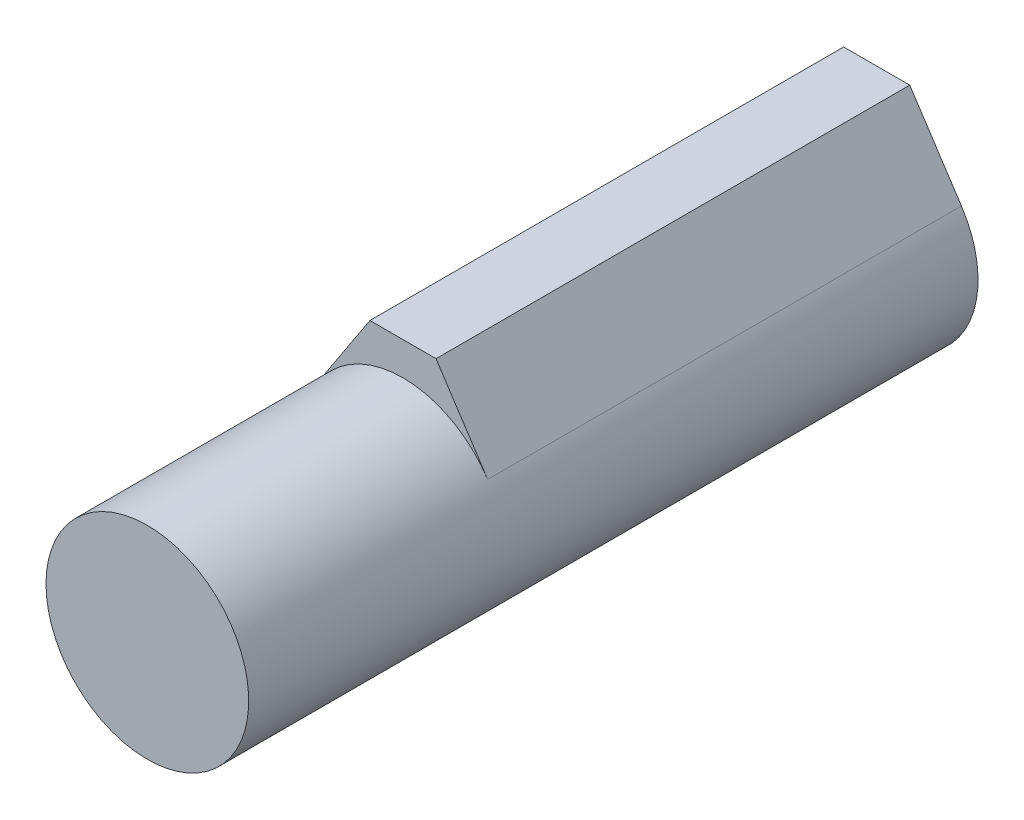
SolidWorks part; units mm, degrees
other "标注1"
sketch "草图4" plane through (-9.2, -9.2, 66.2) normal (-0.7475, -0.0957, 0.6574) x (0.6562, 0.0477, 0.7531)
ref_plane "前视基准面" through (0, 0, 0) normal (0, 0, 1) x (1, 0, 0)
ref_plane "上视基准面" through (0, 0, 0) normal (0, 1, 0) x (1, 0, 0)
ref_plane "右视基准面" through (0, 0, 0) normal (1, 0, 0) x (0, 0, -1)
sketch "草图1" plane through (0, 0, 0) normal (0, 0, 1) x (1, 0, 0)
  line L0 (-3, 12.2) -> (3, 12.2)
  line L5 (-3, 12.2) -> (-7.6927, 5.0461)
  line L6 (3, 12.2) -> (7.6927, 5.0461)
  circle A0 centre (0, 0) radius 9.2 construction
  arc A1 (-7.6927, 5.0461) -> (7.6927, 5.0461) centre (0, 0) ccw
  point P5 (0, 12.2)
  dimension "电池直径" = 18.4
  dimension "D2" = 6
  dimension "D3" = 12.2
extrude "凸台-拉伸3" add sketch "草图1" along normal blind 43
sketch "草图3" plane through (0, 0, 0) normal (0, 0, -1) x (-1, 0, 0)
  circle A0 centre (0, 0) radius 9.2
  dimension "D1" = 18.4
extrude "凸台-拉伸4" add sketch "草图3" against normal blind 66.2
equation "\"D3@草图1\"=\"电池直径\"/2+3mm"
equation "\"D1@草图3\"=\"电池直径\""
